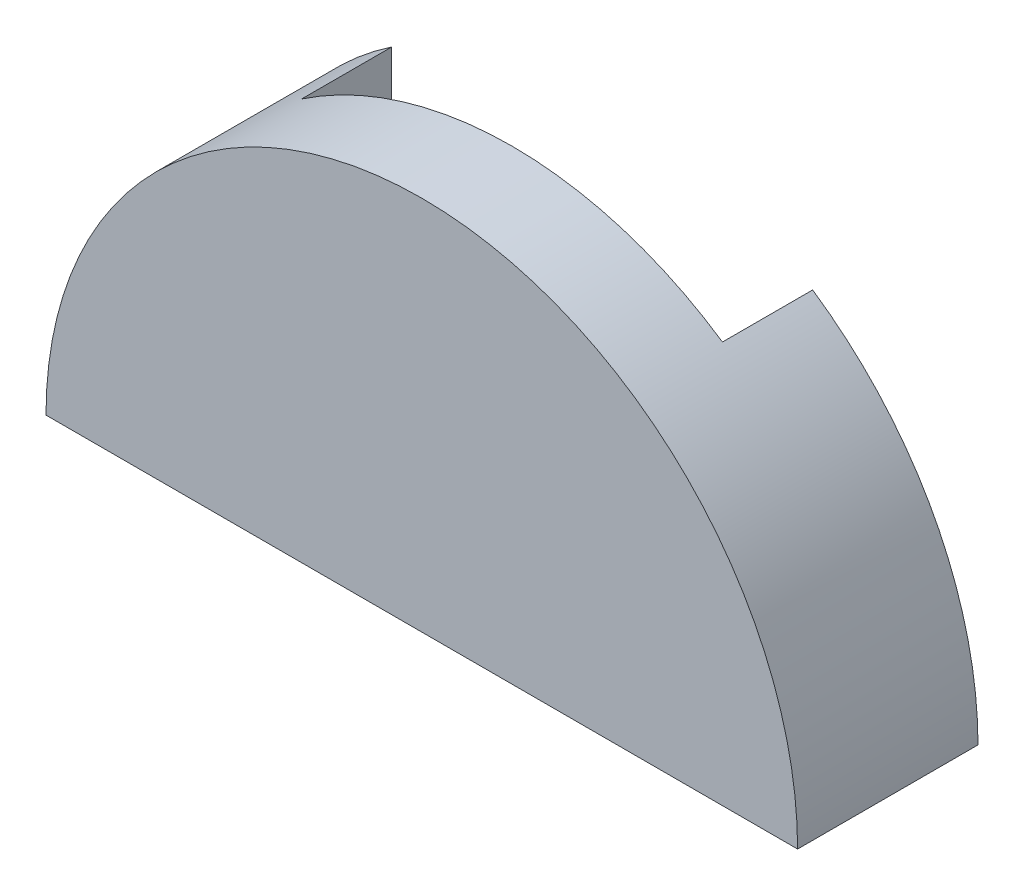
SolidWorks part; units mm, degrees
ref_plane "Front Plane" through (0, 0, 0) normal (0, 0, 1) x (1, 0, 0)
ref_plane "Top Plane" through (0, 0, 0) normal (0, 1, 0) x (1, 0, 0)
ref_plane "Right Plane" through (0, 0, 0) normal (1, 0, 0) x (0, 0, -1)
sketch "Sketch1" plane through (0, 0, 0) normal (0, 0, 1) x (1, 0, 0)
  line L0 (-31.75, 0) -> (31.75, 0)
  circle A0 centre (0, 0) radius 31.75
  point P6 (0, 0)
  dimension "D1" = 63.5
extrude "Boss-Extrude1" add sketch "Sketch1" along normal mid plane 15.24 contours L0 A0
sketch "Sketch2" plane through (0, 0, 0) normal (0, 0, 1) x (1, 0, 0)
  line L1 (-31.75, 0) -> (31.75, 0)
  line L2 (-31.75, 0) -> (31.75, 0)
  line L3 (-17.78, 7.62) -> (17.78, 7.62)
  line L4 (-17.78, 7.62) -> (-17.78, 58.42)
  line L5 (-17.78, 58.42) -> (17.78, 58.42)
  line L6 (17.78, 7.62) -> (17.78, 58.42)
  line L7 (-17.78, 7.62) -> (17.78, 58.42) construction
  line L8 (-17.78, 58.42) -> (17.78, 7.62) construction
  arc A1 (31.75, 0) -> (-31.75, 0) centre (0, 0) ccw
  arc A2 (31.75, 0) -> (-31.75, 0) centre (0, 0) ccw
  point P2 (0, 33.02)
  dimension "D2" = 7.62
  dimension "D3" = 50.8
  dimension "D4" = 35.56
  dimension "D1" = 0
extrude "Cut-Extrude1" cut sketch "Sketch2" against normal blind 7.62 contours L6 A2 L4 L3
